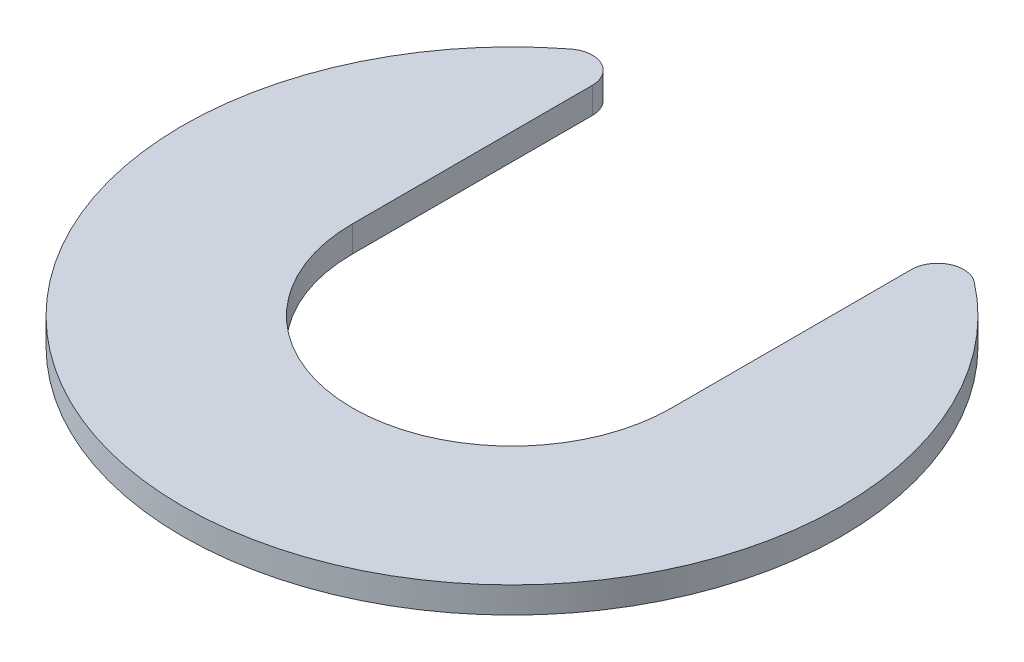
SolidWorks part; units mm, degrees
ref_plane "Front Plane" through (0, 0, 0) normal (0, 0, 1) x (1, 0, 0)
ref_plane "Bottom Plane" through (0, 0, 0) normal (0, 1, 0) x (1, 0, 0)
ref_plane "Right Plane" through (0, 0, 0) normal (1, 0, 0) x (0, 0, -1)
sketch "Sketch1" plane through (0, 0, 0) normal (0, 1, 0) x (1, 0, 0)
  circle A1 centre (0, 0) radius 12.6
  dimension "D1" = 25.2
extrude "Boss-Extrude1" add sketch "Sketch1" along normal blind 1 contours A1
sketch "Sketch2" plane through (0, 0, 0) normal (0, 1, 0) x (1, 0, 0)
  line L0 (0, 0) -> (0, 13.4422) construction
  line L1 (-6.1, 0) -> (-6.1, 13.4422)
  line L2 (6.1, 0) -> (6.1, 13.4422)
  arc A0 (-6.1, 0) -> (6.1, 0) centre (0, 0) ccw
  arc A1 (6.1, 13.4422) -> (-6.1, 13.4422) centre (0, 13.4422) ccw
  point P3 (0, 6.7211)
  dimension "D1" = 6.1
extrude "Cut-Extrude4" cut sketch "Sketch2" against normal through all and the other way through all
fillet "Fillet1" radius 1 2 edges at (6.1, 0.5, -11.025) (-6.1, 0.5, -11.025)
